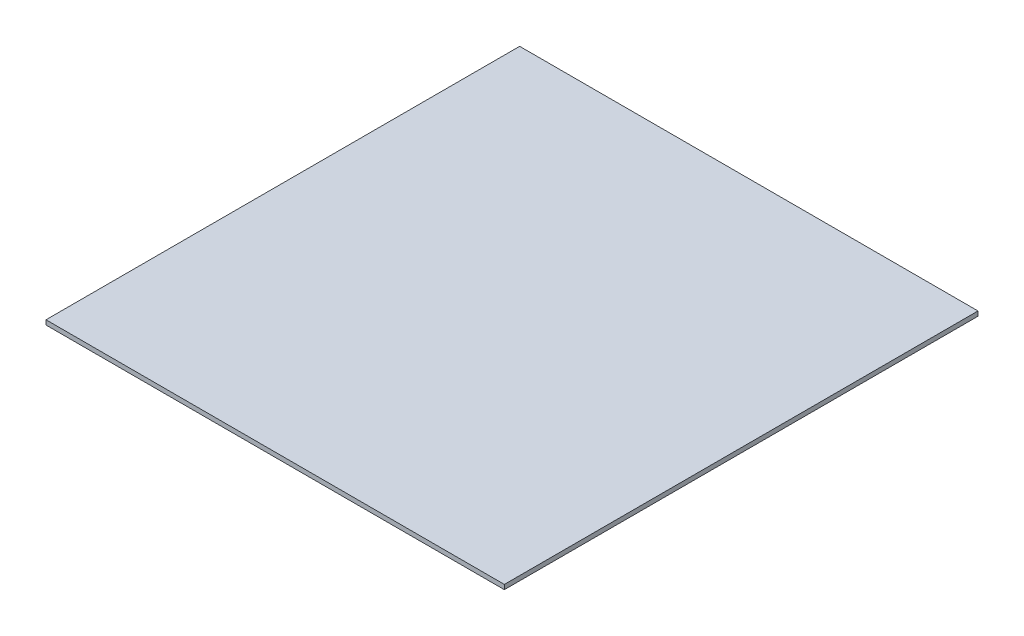
SolidWorks part; units mm, degrees
ref_plane "Front Plane" through (0, 0, 0) normal (0, 0, 1) x (1, 0, 0)
ref_plane "Top Plane" through (0, 0, 0) normal (0, 1, 0) x (1, 0, 0)
ref_plane "Right Plane" through (0, 0, 0) normal (1, 0, 0) x (0, 0, -1)
sketch "Sketch1" plane through (0, 0, 0) normal (0, 1, 0) x (1, 0, 0)
  line L1 (-150, 155) -> (150, 155)
  line L2 (-150, 155) -> (-150, -155)
  line L3 (-150, -155) -> (150, -155)
  line L4 (150, 155) -> (150, -155)
  line L5 (-150, 155) -> (150, -155) construction
  line L6 (-150, -155) -> (150, 155) construction
  point P0 (0, 0)
  dimension "D1" = 300
  dimension "D2" = 310
extrude "Boss-Extrude1" add sketch "Sketch1" along normal blind 3
